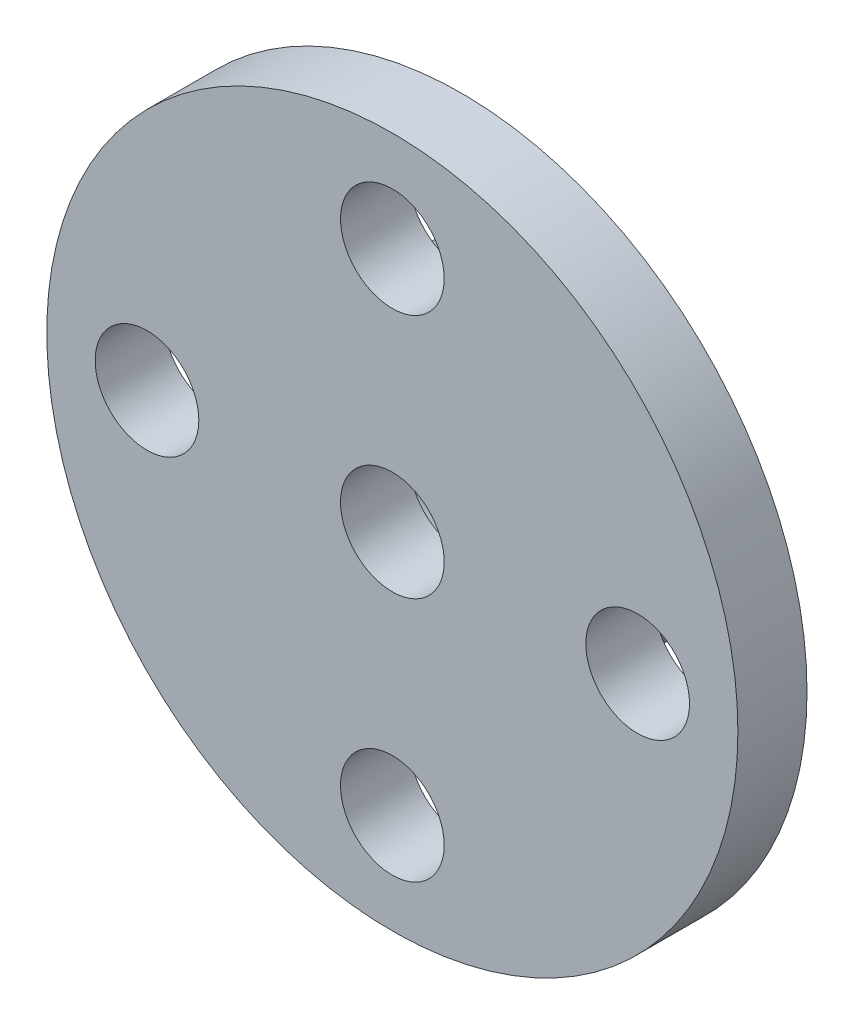
SolidWorks part; units mm, degrees
ref_plane "前视基准面" through (0, 0, 0) normal (0, 0, 1) x (1, 0, 0)
ref_plane "上视基准面" through (0, 0, 0) normal (0, 1, 0) x (1, 0, 0)
ref_plane "右视基准面" through (0, 0, 0) normal (1, 0, 0) x (0, 0, -1)
sketch "草图1" plane through (0, 0, 0) normal (0, 0, 1) x (1, 0, 0)
  circle A0 centre (0, 0) radius 10
  dimension "D1" = 20
extrude "凸台-拉伸1" add sketch "草图1" against normal blind 2 contours A0
sketch "草图2" plane through (0, 0, 0) normal (0, 0, 1) x (1, 0, 0)
  line L0 (-11.7716, 0) -> (10.784, 0) construction
  line L1 (0, 10.5571) -> (0, -11.5447) construction
  circle A0 centre (0, 0) radius 1.5
  circle A1 centre (-7.1, 0) radius 1.5
  circle A2 centre (0, 7.1) radius 1.5
  circle A3 centre (7.1, 0) radius 1.5
  circle A4 centre (0, -7.1) radius 1.5
  point P9 (0, 0)
  point P10 (0, 0)
  point P18 (0, 0)
  dimension "D1" = 3
  dimension "D2" = 3
  dimension "D3" = 7.1
  dimension "D4" = 4
extrude "切除-拉伸1" cut sketch "草图2" against normal up to next
sketch "草图3" plane through (0, 0, -2) normal (0, 0, -1) x (-1, 0, 0)
  circle A0 centre (0, 0) radius 4.75
  circle A1 centre (0, 0) radius 3
  dimension "D1" = 9.5
  dimension "D2" = 6
extrude "凸台-拉伸2" add sketch "草图3" along normal blind 3.5
